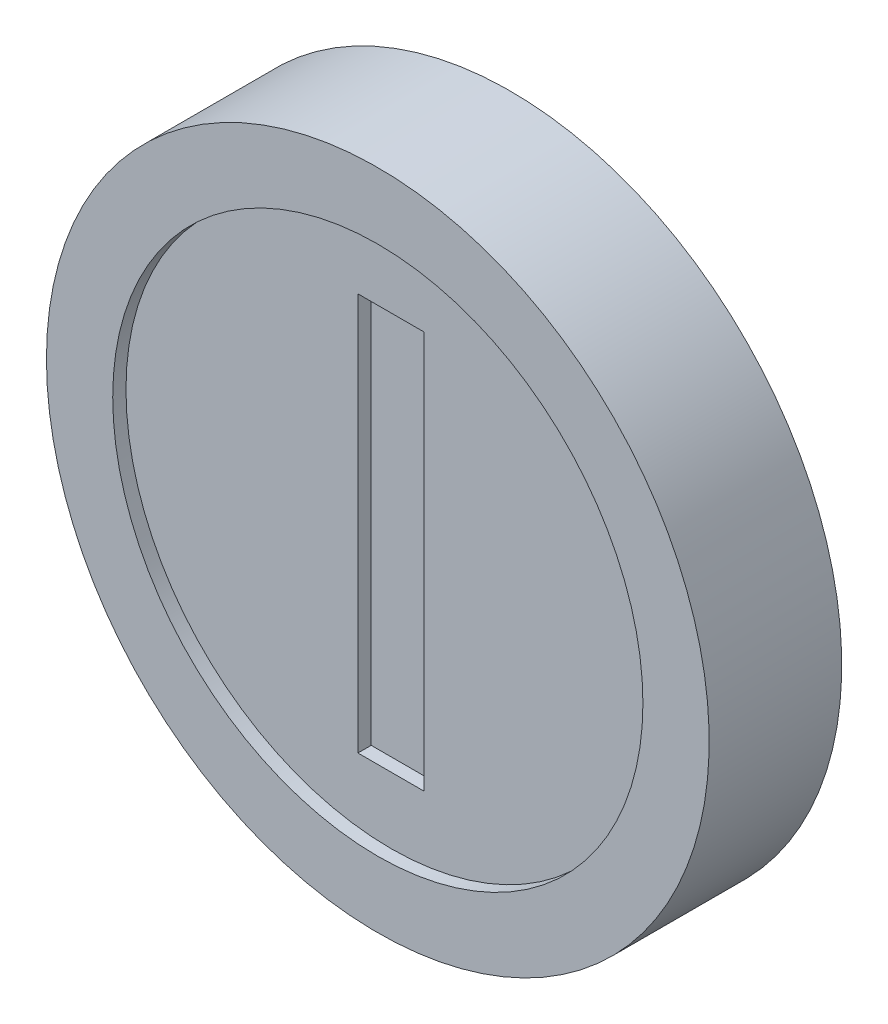
SolidWorks part; units mm, degrees
ref_plane "Front Plane" through (0, 0, 0) normal (0, 0, 1) x (1, 0, 0)
ref_plane "Top Plane" through (0, 0, 0) normal (0, 1, 0) x (1, 0, 0)
ref_plane "Right Plane" through (0, 0, 0) normal (1, 0, 0) x (0, 0, -1)
ref_axis "Axis1" through (0, 0, -88.99) along (0, 0, 1)
sketch "Sketch2" plane through (0, 0, 0) normal (0, 1, 0) x (1, 0, 0)
  line L0 (0, 88.99) -> (0, -88.99) construction
  line L1 (25.4, -5.08) -> (0, -5.08)
  line L2 (25.4, -5.08) -> (25.4, 5.08)
  line L3 (25.4, 5.08) -> (0, 5.08)
  line L4 (0, -5.08) -> (0, 5.08)
  line L5 (25.4, -5.08) -> (0, 5.08) construction
  line L6 (25.4, 5.08) -> (0, -5.08) construction
  line L8 (31.75, -6.35) -> (25.4, -6.35)
  line L9 (31.75, -6.35) -> (31.75, 6.35)
  line L10 (31.75, 6.35) -> (25.4, 6.35)
  line L11 (25.4, -6.35) -> (25.4, 6.35)
  line L12 (31.75, -6.35) -> (25.4, 6.35) construction
  line L13 (31.75, 6.35) -> (25.4, -6.35) construction
  point P0 (12.7, 0)
  point P7 (28.575, 0)
  dimension "D1" = 31.75
  dimension "D2" = 6.35
  dimension "D3" = 10.16
  dimension "D4" = 12.7
revolve "Revolve1" add sketch "Sketch2" angle 360 about axis through (0, 0, -88.99) along (0, 0, 1)
sketch "Sketch3" plane through (0, 0, 5.08) normal (0, 0, 1) x (1, 0, 0)
  line L1 (-3.175, -19.05) -> (3.175, -19.05)
  line L2 (-3.175, -19.05) -> (-3.175, 19.05)
  line L3 (-3.175, 19.05) -> (3.175, 19.05)
  line L4 (3.175, -19.05) -> (3.175, 19.05)
  line L5 (-3.175, -19.05) -> (3.175, 19.05) construction
  line L6 (-3.175, 19.05) -> (3.175, -19.05) construction
  point P0 (0, 0)
  dimension "D1" = 6.35
  dimension "D2" = 38.1
extrude "Cut-Extrude1" cut sketch "Sketch3" against normal blind 1.27
mirror "Mirror1" about plane through (0, 0, 0) normal (0, 0, 1) of "Cut-Extrude1"
equation "\"D1@Sketch2\"=2.5/2"
